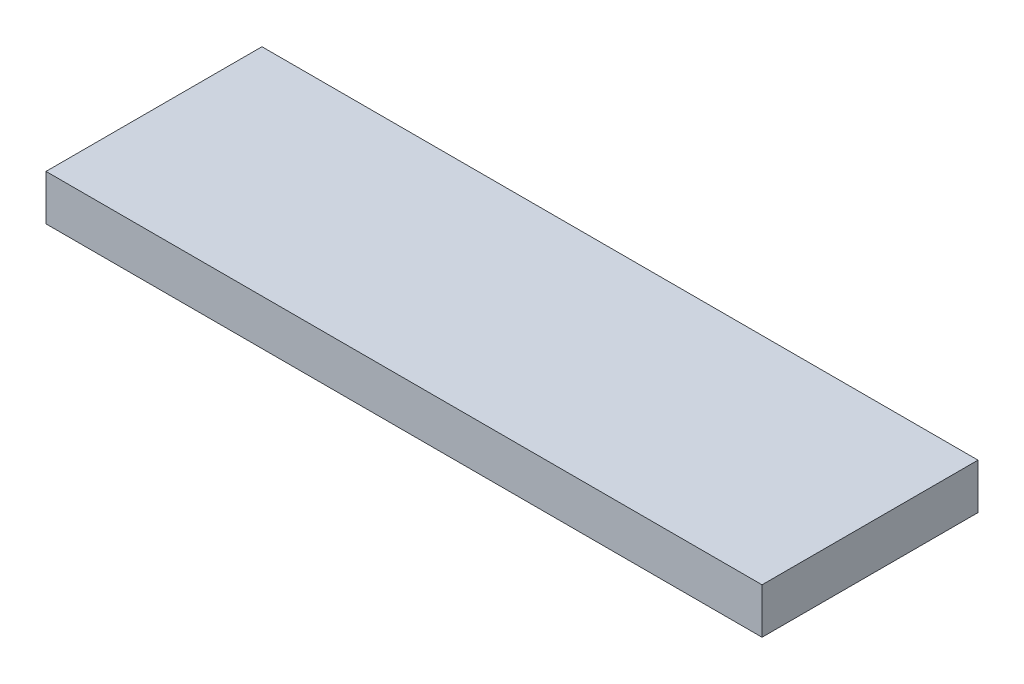
SolidWorks part; units mm, degrees
ref_plane "Front Plane" through (0, 0, 0) normal (0, 0, 1) x (1, 0, 0)
ref_plane "Top Plane" through (0, 0, 0) normal (0, 1, 0) x (1, 0, 0)
ref_plane "Right Plane" through (0, 0, 0) normal (1, 0, 0) x (0, 0, -1)
sketch "Sketch1" plane through (0, 0, 0) normal (0, 1, 0) x (1, 0, 0)
  line L1 (-31.5, -9.5) -> (31.5, -9.5)
  line L2 (-31.5, -9.5) -> (-31.5, 9.5)
  line L3 (-31.5, 9.5) -> (31.5, 9.5)
  line L4 (31.5, -9.5) -> (31.5, 9.5)
  line L5 (-31.5, -9.5) -> (31.5, 9.5) construction
  line L6 (-31.5, 9.5) -> (31.5, -9.5) construction
  point P0 (0, 0)
  dimension "D1" = 19
  dimension "D2" = 63
extrude "Boss-Extrude1" add sketch "Sketch1" along normal blind 4
